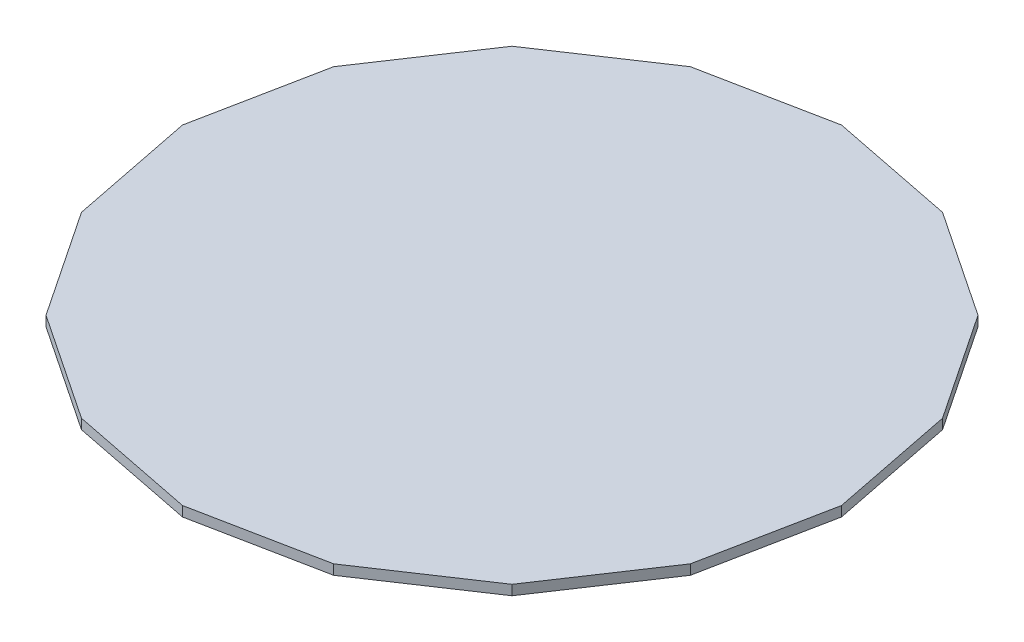
SolidWorks part; units mm, degrees
ref_plane "Front Plane" through (0, 0, 0) normal (0, 0, 1) x (1, 0, 0)
ref_plane "Top Plane" through (0, 0, 0) normal (0, 1, 0) x (1, 0, 0)
ref_plane "Right Plane" through (0, 0, 0) normal (1, 0, 0) x (0, 0, -1)
sketch "Sketch1" plane through (0, 0, 0) normal (0, 1, 0) x (1, 0, 0)
  line L1 (66.2734, 0) -> (61.2287, 25.3617)
  line L2 (61.2287, 25.3617) -> (46.8624, 46.8624)
  line L3 (46.8624, 46.8624) -> (25.3617, 61.2287)
  line L4 (25.3617, 61.2287) -> (0, 66.2734)
  line L5 (0, 66.2734) -> (-25.3617, 61.2287)
  line L6 (-25.3617, 61.2287) -> (-46.8624, 46.8624)
  line L7 (-46.8624, 46.8624) -> (-61.2287, 25.3617)
  line L8 (-61.2287, 25.3617) -> (-66.2734, 0)
  line L9 (-66.2734, 0) -> (-61.2287, -25.3617)
  line L10 (-61.2287, -25.3617) -> (-46.8624, -46.8624)
  line L11 (-46.8624, -46.8624) -> (-25.3617, -61.2287)
  line L12 (-25.3617, -61.2287) -> (0, -66.2734)
  line L13 (0, -66.2734) -> (25.3617, -61.2287)
  line L14 (25.3617, -61.2287) -> (46.8624, -46.8624)
  line L15 (46.8624, -46.8624) -> (61.2287, -25.3617)
  line L16 (61.2287, -25.3617) -> (66.2734, 0)
  circle A0 centre (0, 0) radius 65 construction
  point P1 (0, 0)
  dimension "D1" = 130
extrude "Boss-Extrude1" add sketch "Sketch1" along normal blind 2
